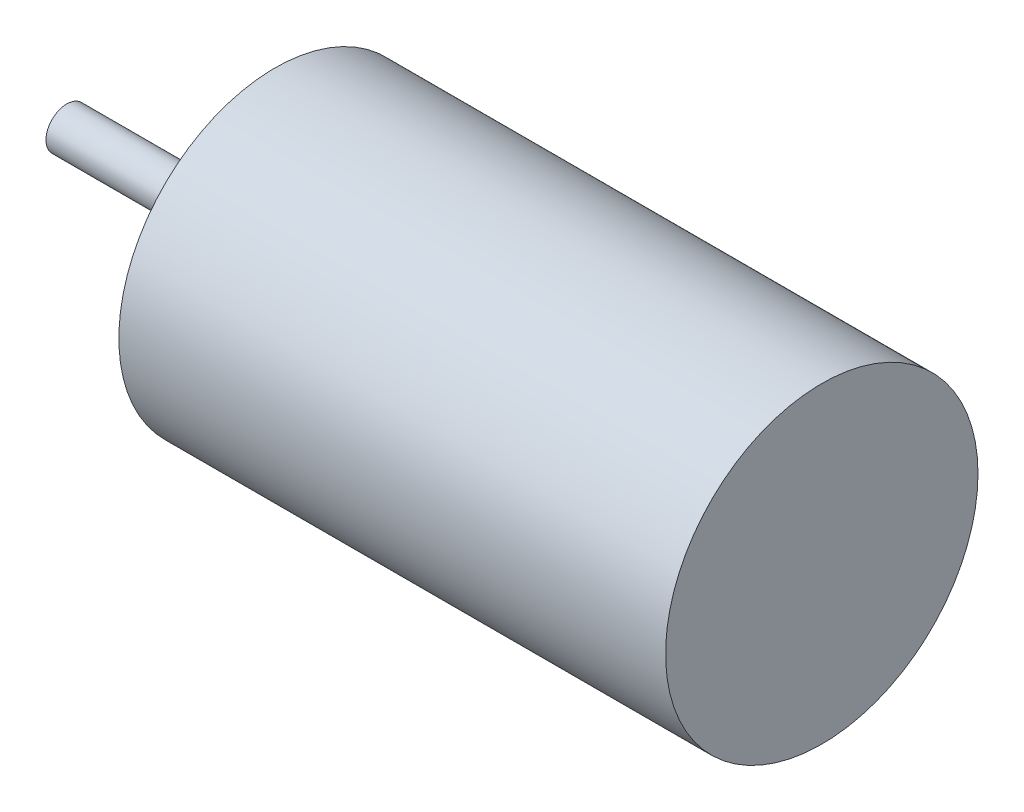
SolidWorks part; units mm, degrees
ref_plane "Front Plane" through (0, 0, 0) normal (0, 0, 1) x (1, 0, 0)
ref_plane "Top Plane" through (0, 0, 0) normal (0, 1, 0) x (1, 0, 0)
ref_plane "Right Plane" through (0, 0, 0) normal (1, 0, 0) x (0, 0, -1)
sketch "Sketch1" plane through (0, 0, 0) normal (0, 1, 0) x (1, 0, 0)
  line L0 (0, 0) -> (-14.5, 0)
  line L1 (-14.5, 0) -> (-14.5, 0.4)
  line L2 (-14.5, 0.4) -> (-10.5, 0.4)
  line L3 (-10.5, 0.4) -> (-10.5, 3)
  line L4 (-10.5, 3) -> (0, 3)
  line L10 (0, 3) -> (0, 0)
  dimension "D1" = 0.4
  dimension "16" = 3
  dimension "D2" = 10.5
  dimension "D3" = 4
revolve "Revolve1" add sketch "Sketch1" angle 360 about L0
